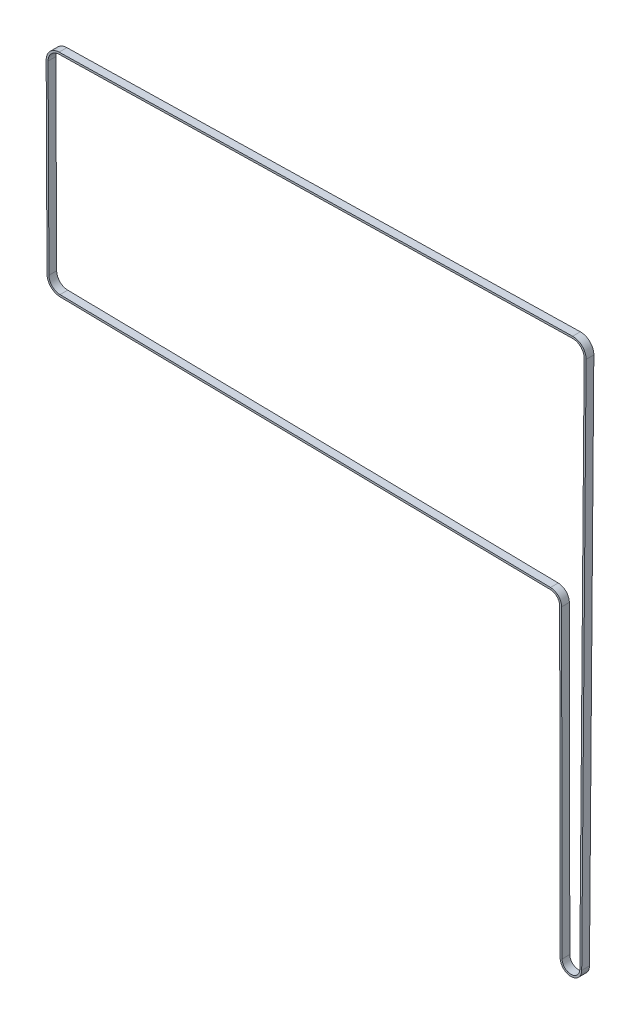
SolidWorks part; units mm, degrees
material "Резина"
ref_plane "Спереди" through (0, 0, 0) normal (0, 0, 1) x (1, 0, 0)
ref_plane "Сверху" through (0, 0, 0) normal (0, 1, 0) x (1, 0, 0)
ref_plane "Справа" through (0, 0, 0) normal (1, 0, 0) x (0, 0, -1)
sketch "Эскиз1" plane through (0, 0, 0) normal (0, 0, 1) x (1, 0, 0)
  line B0 (6.8585, -0.0565) -> (10.2497, 411.928)
  line B1 (1.3179, 420.7481) -> (-396.8293, 412.4586)
  line B2 (-405.3971, 403.671) -> (-404.7499, 260.1848)
  line B3 (-396.1496, 251.4756) -> (-15.8504, 244.973)
  line B4 (-7.25, 236.2388) -> (-6.8587, -0.0114)
  arc B5 (-6.8587, -0.0114) -> (6.8585, -0.0565) centre (0, 0) ccw
  arc B6 (10.2497, 411.928) -> (1.3179, 420.7481) centre (1.5, 412) ccw
  arc B7 (-396.8293, 412.4586) -> (-405.3971, 403.671) centre (-396.6472, 403.7105) ccw
  arc B8 (-404.7499, 260.1848) -> (-396.1496, 251.4756) centre (-396, 260.2243) ccw
  arc B9 (-15.8504, 244.973) -> (-7.25, 236.2388) centre (-16, 236.2243) cw
sketch_block_instance "Блок-ремень2-1"
sketch_block "Блок-ремень2"
extrude "Вытянуть-Тонкостенный1" add sketch "Эскиз1" along normal blind 6 thin
